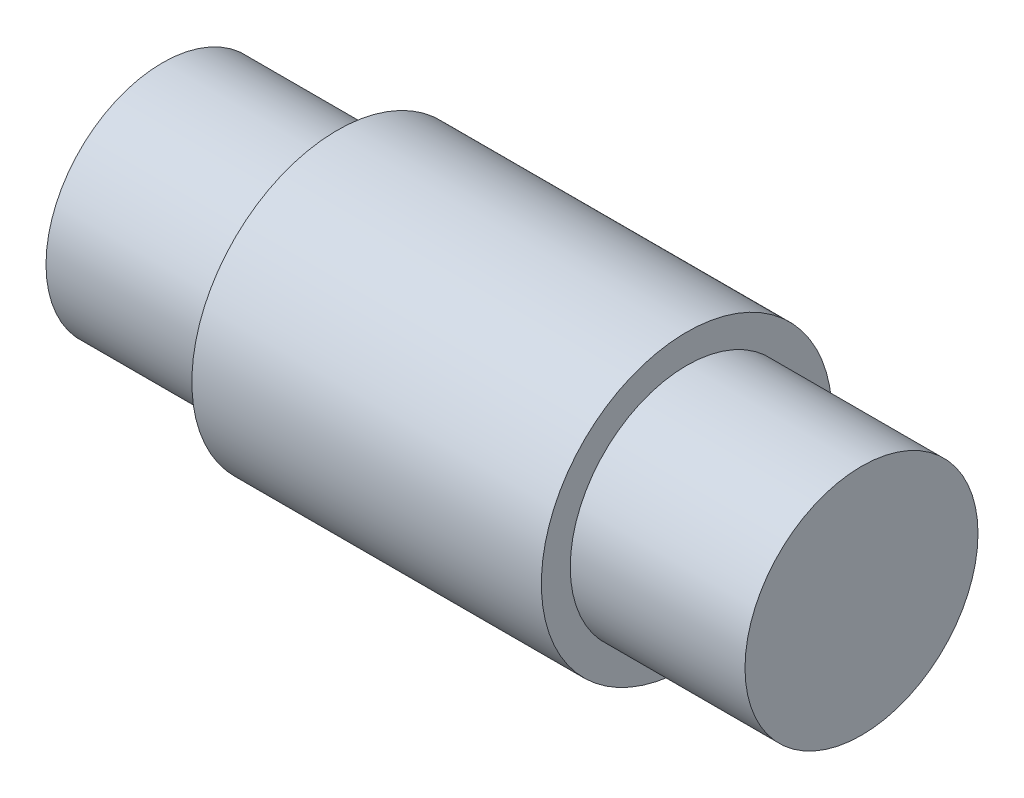
SolidWorks part; units mm, degrees
ref_plane "Front Plane" through (0, 0, 0) normal (0, 0, 1) x (1, 0, 0)
ref_plane "Top Plane" through (0, 0, 0) normal (0, 1, 0) x (1, 0, 0)
ref_plane "Right Plane" through (0, 0, 0) normal (1, 0, 0) x (0, 0, -1)
sketch "Sketch1" plane through (0, 0, 0) normal (0, 0, 1) x (1, 0, 0)
  line L0 (0, 0) -> (-5256.5397, 0) construction
  line L1 (0, 0) -> (0, 3.9624)
  line L2 (-4.7625, 0) -> (4.7625, 0)
  line L3 (-4.7625, 3.9624) -> (4.7625, 3.9624)
  line L4 (4.7625, 0) -> (4.7625, 3.9624)
  line L5 (4.7625, 0) -> (4.7625, 3.175)
  line L6 (4.7625, 0) -> (9.525, 0)
  line L7 (4.7625, 3.175) -> (9.525, 3.175)
  line L8 (9.525, 0) -> (9.525, 3.175)
  line L9 (0, 0) -> (0, 5256.5397) construction
  line L10 (-4.7625, 0) -> (-9.525, 0)
  line L11 (-9.525, 0) -> (-9.525, 3.175)
  line L12 (-4.7625, 3.175) -> (-9.525, 3.175)
  line L13 (-4.7625, 0) -> (-4.7625, 3.9624)
  dimension "D1" = 4.7625
  dimension "D2" = 4.7625
  dimension "D3" = 3.9624
  dimension "D4" = 3.175
revolve "Revolve1" add sketch "Sketch1" angle 360 about L0
